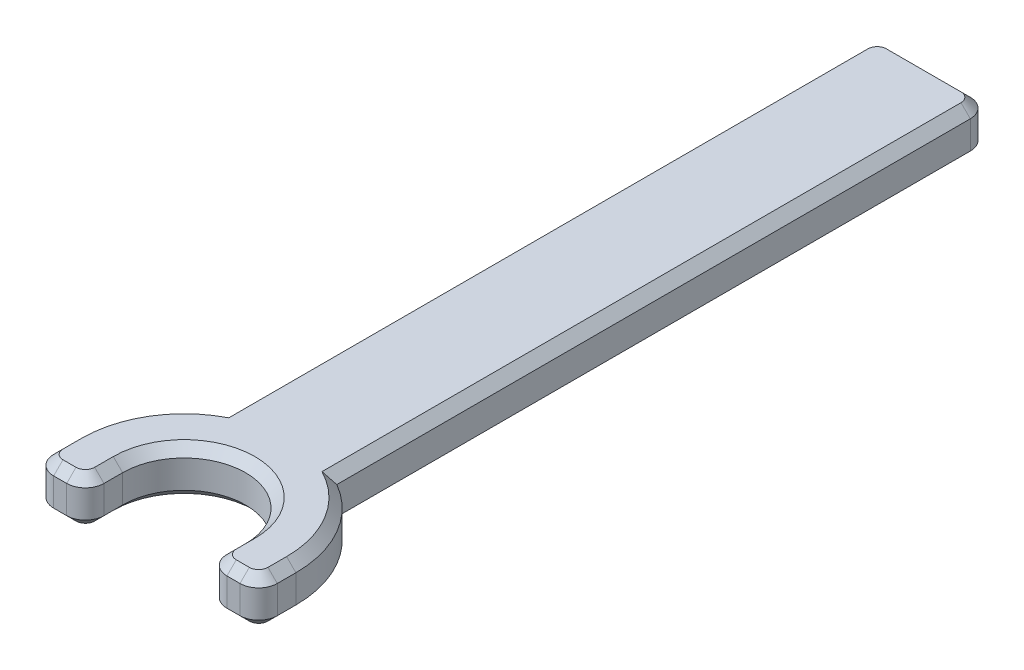
SolidWorks part; units mm, degrees
ref_plane "Front Plane" through (0, 0, 0) normal (0, 0, 1) x (1, 0, 0)
ref_plane "Top Plane" through (0, 0, 0) normal (0, 1, 0) x (1, 0, 0)
ref_plane "Right Plane" through (0, 0, 0) normal (1, 0, 0) x (0, 0, -1)
sketch "Sketch1" plane through (0, 0, 0) normal (0, 1, 0) x (1, 0, 0)
  line L0 (-3.3, 0) -> (-3.3, -2)
  line L1 (-3.3, -2) -> (-6, -2)
  line L2 (-6, -2) -> (-6, 0)
  line L3 (0, 18.2691) -> (0, -3.3) construction
  line L4 (-3, 40.1962) -> (-3, 5.1962)
  line L5 (-3, 40.1962) -> (3, 40.1962)
  line L6 (3, 40.1962) -> (3, 5.1962)
  line L7 (6, -2) -> (6, 0)
  line L8 (3.3, 0) -> (3.3, -2)
  line L9 (3.3, -2) -> (6, -2)
  circle A0 centre (0, 0) radius 3.3 construction
  arc A1 (-3.3, 0) -> (3.3, 0) centre (0, 0) cw
  arc A2 (-6, 0) -> (-3, 5.1962) centre (0, 0) cw
  arc A3 (6, 0) -> (3, 5.1962) centre (0, 0) ccw
  point P9 (0, 0)
  point P12 (0, 0)
  point P13 (-6, 0)
  point P15 (-3, 5.1962)
  point P16 (-3.3, 0)
  point P17 (-6, -2)
  point P18 (-3, 5.1962)
  point P19 (0, 20.1962)
  point P21 (-3.3, -2)
  point P22 (0, 0)
  point P23 (0, 0)
  point P24 (-3.3, 0)
  point P25 (0, 0)
  point P27 (0, 40.1962)
  dimension "D1" = 6.6
  dimension "D2" = 12
  dimension "D3" = 6
  dimension "D5" = 2
  dimension "D6" = 35
extrude "Boss-Extrude1" add sketch "Sketch1" along normal blind 2.5
fillet "Fillet1" radius 1 6 edges at (-3, 1.25, -40.1962) (3, 1.25, -40.1962) (6, 1.25, 2) (3.3, 1.25, 2) (-3.3, 1.25, 2) (-6, 1.25, 2)
chamfer "Chamfer1" distance 0.5 angle 45 36 edges at (-5.1962, 0, -3) (-6, 0, 0.5) (-5.7071, 0, 1.7071) (-4.65, 0, 2) (-3.5929, 0, 1.7071) (-3.3, 0, 0.5) (0, 0, -3.3) (3.3, 0, 0.5) (3.5929, 0, 1.7071) (4.65, 0, 2) (5.7071, 0, 1.7071) (6, 0, 0.5) (5.1962, 0, -3) (3, 0, -22.1962) (2.7071, 0, -39.9033) (0, 0, -40.1962) (-2.7071, 0, -39.9033) (-3, 0, -22.1962) (2.7071, 2.5, -39.9033) (3, 2.5, -22.1962) (5.1962, 2.5, -3) (6, 2.5, 0.5) (5.7071, 2.5, 1.7071) (4.65, 2.5, 2) (3.5929, 2.5, 1.7071) (3.3, 2.5, 0.5) (0, 2.5, -3.3) (-3.3, 2.5, 0.5) (-3.5929, 2.5, 1.7071) (-4.65, 2.5, 2) (-5.7071, 2.5, 1.7071) (-6, 2.5, 0.5) (-5.1962, 2.5, -3) (-3, 2.5, -22.1962) (-2.7071, 2.5, -39.9033) (0, 2.5, -40.1962)
